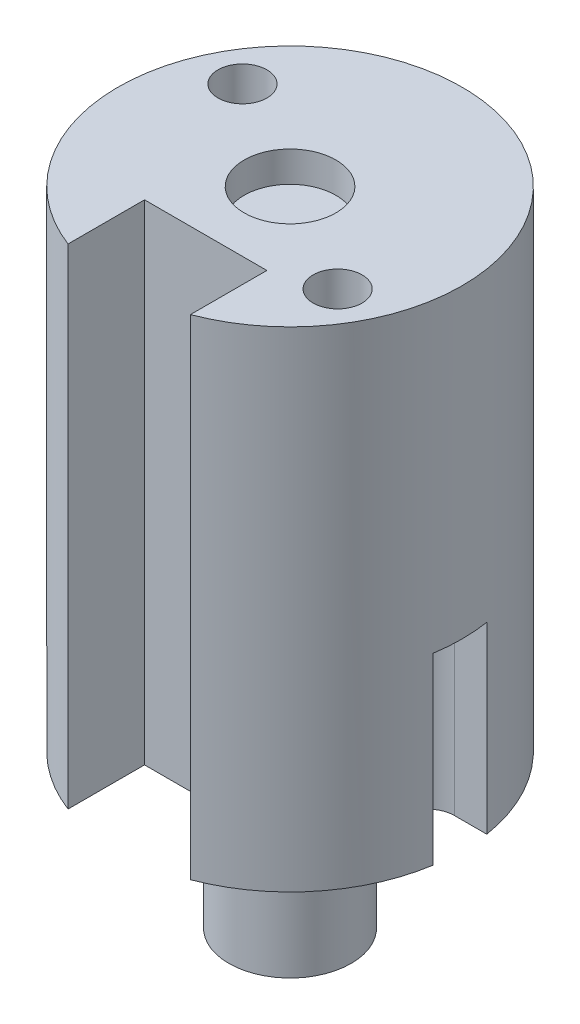
SolidWorks part; units mm, degrees
ref_plane "前视基准面" through (0, 0, 0) normal (0, 0, 1) x (1, 0, 0)
ref_plane "上视基准面" through (0, 0, 0) normal (0, 1, 0) x (1, 0, 0)
ref_plane "右视基准面" through (0, 0, 0) normal (1, 0, 0) x (0, 0, -1)
sketch "草图1" plane through (0, 0, 0) normal (0, 1, 0) x (1, 0, 0)
  circle A0 centre (0, 0) radius 11.25
  dimension "D1" = 22.5
extrude "凸台-拉伸1" add sketch "草图1" along normal blind 32
sketch "草图3" plane through (0, 0, 0) normal (0, -1, 0) x (1, 0, 0)
  line L0 (0, 0) -> (0, 8.32) construction
  line L1 (0, 0) -> (9, 0) construction
  circle A0 centre (9, 0) radius 1.21
  circle A1 centre (-9, 0) radius 1.21
  dimension "D1" = 2.42
  dimension "D2" = 18
extrude "切除-拉伸1" cut sketch "草图3" against normal blind 30
sketch "草图4" plane through (0, 0, 0) normal (0, -1, 0) x (1, 0, 0)
  circle A0 centre (0, 0) radius 4
  dimension "D1" = 8
extrude "凸台-拉伸2" add sketch "草图4" along normal blind 10
sketch "草图5" plane through (0, -10, 0) normal (0, -1, 0) x (1, 0, 0)
  line L0 (0, 0) -> (0, 2.9098) construction
  line L1 (0, -2.9098) -> (2.52, -1.4549)
  line L2 (2.52, -1.4549) -> (2.52, 1.4549)
  line L3 (2.52, 1.4549) -> (0, 2.9098)
  line L4 (0, 2.9098) -> (-2.52, 1.4549)
  line L5 (-2.52, 1.4549) -> (-2.52, -1.4549)
  line L6 (-2.52, -1.4549) -> (0, -2.9098)
  circle A1 centre (0, 0) radius 2.52 construction
  dimension "D1" = 5.04
extrude "切除-拉伸2" cut sketch "草图5" against normal blind 10
chamfer "倒角1" distance 1 angle 45 1 edges at (0, 0, 4)
chamfer "倒角2" [suppressed] distance 4 angle 45
sketch "草图6" plane through (0, 32, 0) normal (0, 1, 0) x (1, 0, 0)
  line L0 (0, 0) -> (0, -8.0149) construction
  line L2 (-4, -5.5149) -> (4, -5.5149)
  line L3 (-4, -5.5149) -> (-4, -10.5149)
  line L4 (-4, -10.5149) -> (4, -10.5149)
  line L5 (4, -5.5149) -> (4, -10.5149)
  line L6 (-4, -5.5149) -> (4, -10.5149) construction
  line L7 (-4, -10.5149) -> (4, -5.5149) construction
  circle A0 centre (0, 0) radius 11.25 construction
  circle A1 centre (0, 0) radius 11.25
  circle M4 centre (0, 0) radius 11.25
  dimension "D1" = 8
  dimension "D2" = 5
extrude "切除-拉伸3" cut sketch "草图6" against normal through all contours L5 L2 L3 L4 | L4 M4
sketch "草图7" plane through (0, 32, 0) normal (0, 1, 0) x (1, 0, 0)
  line L0 (0, 0) -> (0, 6.2983) construction
  line L1 (0, 0) -> (-7.3612, 4.25) construction
  line L2 (0, 0) -> (5.6388, 9.7667) construction
  circle A0 centre (-7.3612, 4.25) radius 1.6
  circle A1 centre (7.3612, -4.25) radius 1.6
  circle A2 centre (9, 0) radius 1.21 construction
  circle A3 centre (-9, 0) radius 1.21 construction
  circle A4 centre (9, 0) radius 1.21 construction
  circle A5 centre (-9, 0) radius 1.21 construction
  dimension "D2" = 3.2
  dimension "D1" = 60
  dimension "D3" = 17
extrude "切除-拉伸4" cut sketch "草图7" against normal blind 6
sketch "草图8" plane through (0, 32, 0) normal (0, 1, 0) x (1, 0, 0)
  circle A0 centre (0, 0) radius 3
  dimension "D1" = 6
extrude "切除-拉伸5" cut sketch "草图8" against normal blind 2
sketch "草图9" plane through (0, 0, 0) normal (0, -1, 0) x (1, 0, 0)
  line L0 (0, 0) -> (0, 10.415) construction
  line L1 (-9, 0) -> (-15.0353, 0) construction
  line L2 (21.0706, -1.75) -> (21.0706, 1.75)
  line L3 (-21.0706, -1.75) -> (-9, -1.75)
  line L4 (-21.0706, -1.75) -> (-21.0706, 1.75)
  line L5 (-21.0706, 1.75) -> (-9, 1.75)
  line L6 (-9, -1.75) -> (-9, 1.75)
  line L7 (-21.0706, -1.75) -> (-9, 1.75) construction
  line L8 (-21.0706, 1.75) -> (-9, -1.75) construction
  line L9 (21.0706, -1.75) -> (9, -1.75)
  line L10 (9, -1.75) -> (9, 1.75)
  line L11 (21.0706, 1.75) -> (9, 1.75)
  circle A0 centre (-9, 0) radius 1.75
  circle A1 centre (9, 0) radius 1.75
  circle M1 centre (-9, 0) radius 1.21
  circle M2 centre (9, 0) radius 1.21
  arc M7 (-4, 10.5149) -> (4, 10.5149) centre (0, 0) ccw
  dimension "D1" = 3.5
extrude "切除-拉伸6" cut sketch "草图9" against normal blind 12 contours A0 L5 L3 M7 | L6 A0 M1 | L6 A0 M1 | L10 A1 M2 | A1 L9 L11 M7 | L10 A1 M2
